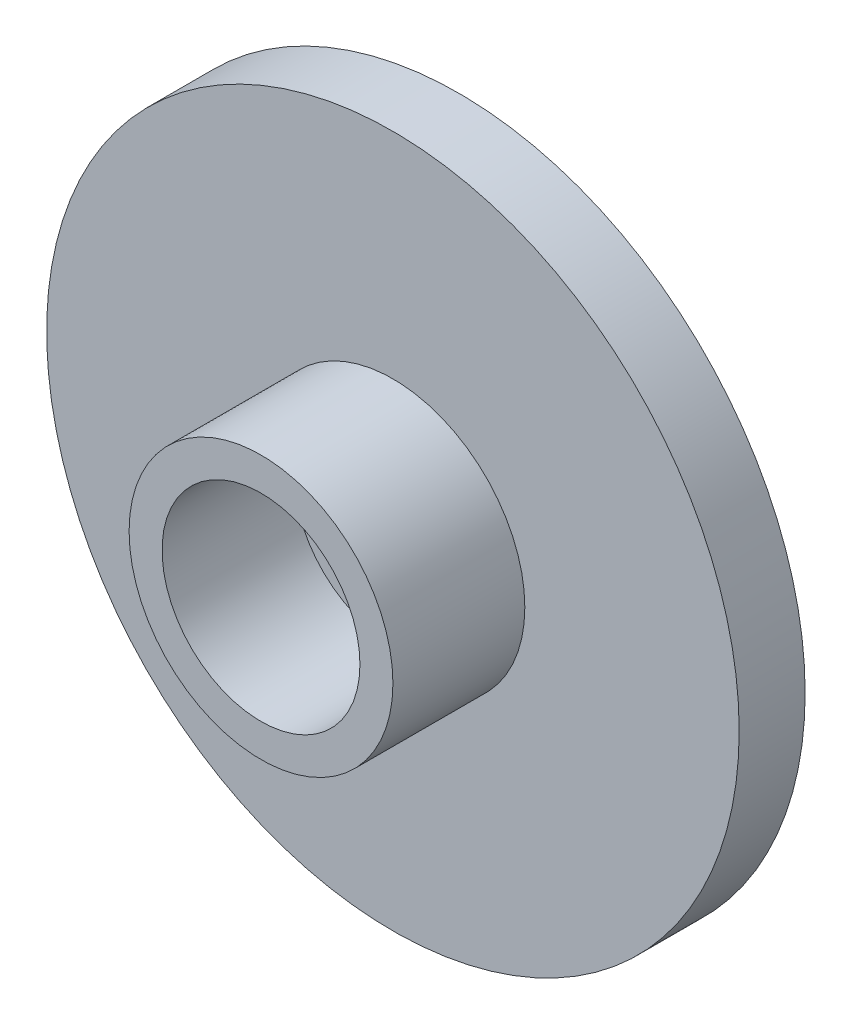
SolidWorks part; units mm, degrees
ref_plane "前视基准面" through (0, 0, 0) normal (0, 0, 1) x (1, 0, 0)
ref_plane "上视基准面" through (0, 0, 0) normal (0, 1, 0) x (1, 0, 0)
ref_plane "右视基准面" through (0, 0, 0) normal (1, 0, 0) x (0, 0, -1)
sketch "草图1" plane through (0, 0, 0) normal (0, 1, 0) x (1, 0, 0)
  line L0 (10.5, 0) -> (0, 0)
  line L1 (0, 0) -> (0, -2)
  line L2 (0, -2) -> (3, -2)
  line L3 (3, -2) -> (3, -6)
  line L4 (3, -6) -> (4, -6)
  line L5 (4, -6) -> (4, -2)
  line L6 (4, -2) -> (10.5, -2)
  line L7 (10.5, -2) -> (10.5, 0)
  line L8 (0, 0) -> (0, -6) construction
revolve "旋转1" add sketch "草图1" angle 360 about L8
